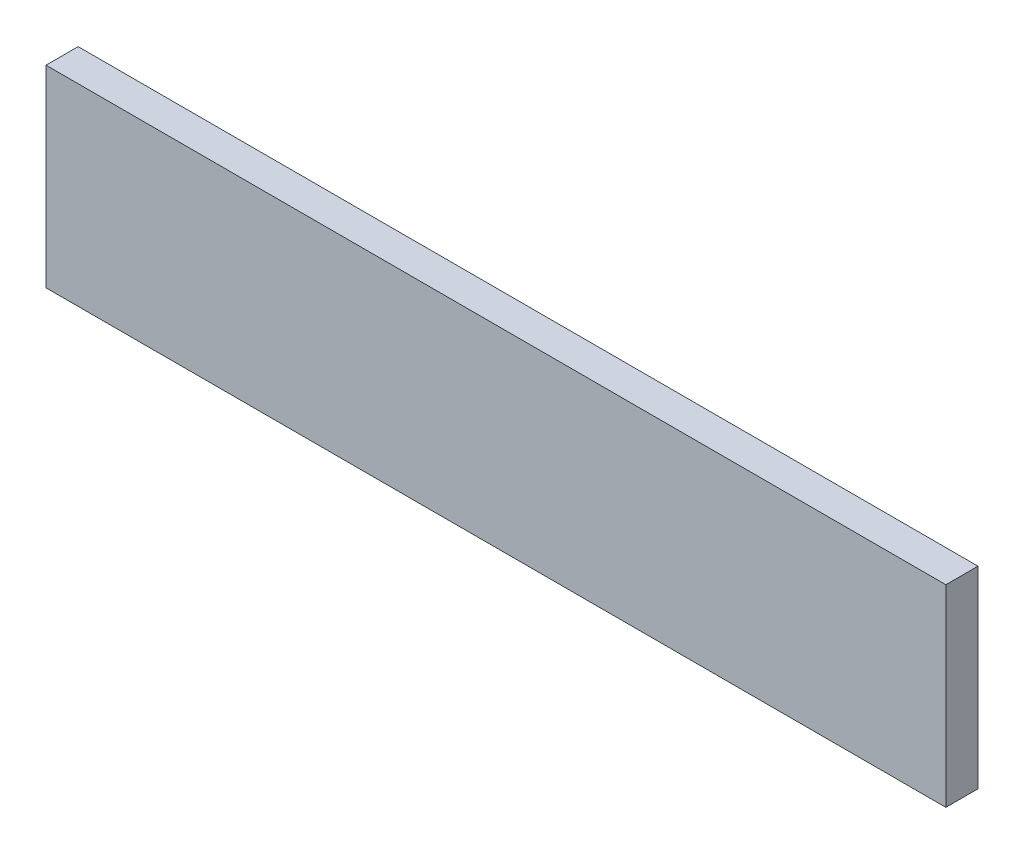
SolidWorks part; units mm, degrees
material "1060 Alloy"
ref_plane "Front Plane" through (0, 0, 0) normal (0, 0, 1) x (1, 0, 0)
ref_plane "Top Plane" through (0, 0, 0) normal (0, 1, 0) x (1, 0, 0)
ref_plane "Right Plane" through (0, 0, 0) normal (1, 0, 0) x (0, 0, -1)
sketch "Sketch1" plane through (0, 0, 0) normal (0, 0, 1) x (1, 0, 0)
  line L1 (-42, -9) -> (42, -9)
  line L2 (-42, -9) -> (-42, 9)
  line L3 (-42, 9) -> (42, 9)
  line L4 (42, -9) -> (42, 9)
  line L5 (-42, -9) -> (42, 9) construction
  line L6 (-42, 9) -> (42, -9) construction
  point P0 (0, 0)
  dimension "D1" = 84
  dimension "D2" = 18
extrude "Boss-Extrude1" add sketch "Sketch1" along normal blind 3
